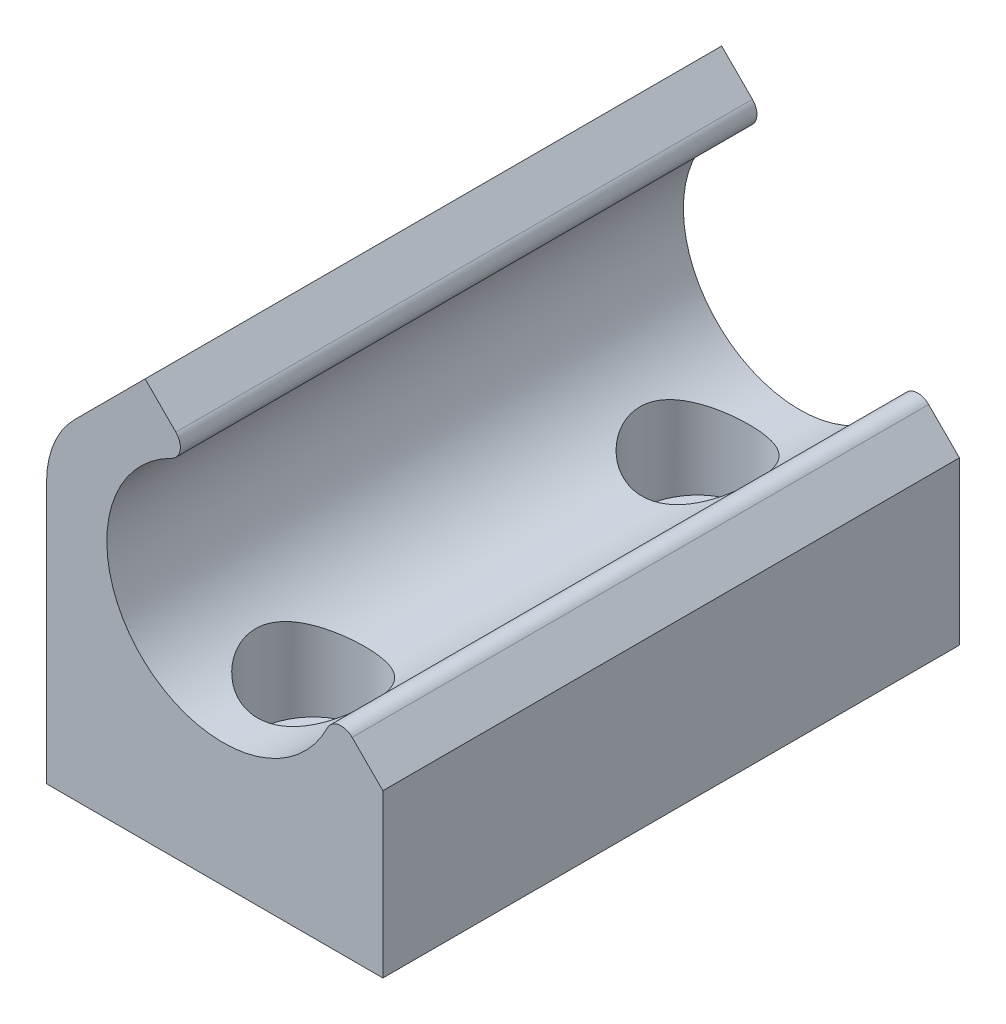
SolidWorks part; units mm, degrees
ref_plane "Front Plane" through (0, 0, 0) normal (0, 0, 1) x (1, 0, 0)
ref_plane "Top Plane" through (0, 0, 0) normal (0, 1, 0) x (1, 0, 0)
ref_plane "Right Plane" through (0, 0, 0) normal (1, 0, 0) x (0, 0, -1)
sketch "Sketch1" plane through (0, 0, 0) normal (0, 0, 1) x (1, 0, 0)
  line L0 (0, 0) -> (17.5, 0)
  line L1 (17.5, 0) -> (17.5, 8.44)
  line L2 (17.5, 8.44) -> (15.0251, 10.9149)
  line L3 (7.6032, 18.3368) -> (5.1283, 20.8117)
  line L4 (5.1283, 20.8117) -> (0, 15.6833)
  line L5 (0, 15.6833) -> (0, 0)
  arc A0 (15.0251, 10.9149) -> (7.6032, 18.3368) centre (9.1858, 12.4974) cw
  dimension "D1" = 6.05
  dimension "D2" = 3.5
  dimension "D3" = 17.5
  dimension "D4" = 8.44
  dimension "D5" = 3.01
  dimension "D6" = 45
extrude "Boss-Extrude1" add sketch "Sketch1" along normal blind 30
fillet "Fillet1" radius 0.8 2 edges at (15.0251, 10.9149, 15) (7.6032, 18.3368, 15)
ref_plane "Plane1" through (0, 9.8284, 0) normal (0, -1, 0) x (-1, 0, 0)
sketch "Sketch3" plane through (0, 9.8284, 0) normal (0, -1, 0) x (-1, 0, 0)
  line L0 (-3.1358, 0) -> (-14.6152, 0) construction
  line L1 (-3.1358, 0) -> (-14.6152, 0) construction
  circle A0 centre (-8.8755, -5) radius 3
  circle A1 centre (-8.8755, -25) radius 3
  point P7 (-8.8755, 0)
  dimension "D1" = 6
  dimension "D2" = 5
  dimension "D3" = 20
extrude "Cut-Extrude1" cut sketch "Sketch3" along normal blind 7
sketch "Sketch4" plane through (0, 9.8284, 0) normal (0, -1, 0) x (-1, 0, 0)
  circle A0 centre (-8.8755, -5) radius 1.55
  circle A1 centre (-8.8755, -25) radius 1.55
  dimension "D1" = 3.1
  dimension "D2" = 3.1
extrude "Cut-Extrude2" cut sketch "Sketch4" along normal through all
fillet "Fillet2" radius 5 1 edges at (0, 15.6833, 15)
